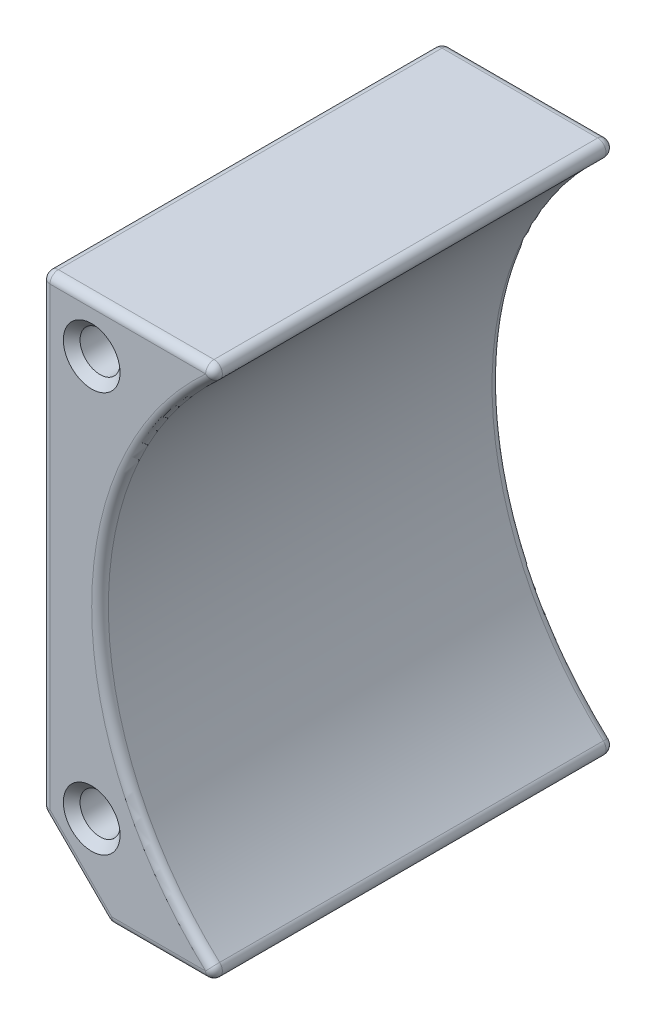
SolidWorks part; units mm, degrees
ref_plane "Front Plane" through (0, 0, 0) normal (0, 0, 1) x (1, 0, 0)
ref_plane "Top Plane" through (0, 0, 0) normal (0, 1, 0) x (1, 0, 0)
ref_plane "Right Plane" through (0, 0, 0) normal (1, 0, 0) x (0, 0, -1)
sketch "Sketch1" plane through (0, 0, 0) normal (0, 0, 1) x (1, 0, 0)
  line L1 (0, 0) -> (17.7546, 0)
  line L2 (0, 0) -> (0, 50.8)
  line L3 (0, 50.8) -> (17.7546, 50.8)
  arc A0 (17.7546, 50.8) -> (17.7546, 0) centre (38.1, 25.4) ccw
  dimension "D4" = 65.0875
  dimension "D1" = 50.8
  dimension "D2" = 25.4
  dimension "D3" = 38.1
extrude "Boss-Extrude1" add sketch "Sketch1" along normal blind 38.1
sketch "Sketch2" plane through (0, 0, 38.1) normal (0, 0, 1) x (1, 0, 0)
  line L0 (17.7546, 50.8) -> (0, 50.8) construction
  line L1 (0, 50.8) -> (0, 0) construction
  line L2 (0, 0) -> (17.7546, 0) construction
  circle A0 centre (4.7625, 46.0375) radius 1.905
  circle A1 centre (4.7625, 7.9375) radius 1.905
  dimension "D4" = 3.81
  dimension "D1" = 4.7625
  dimension "D2" = 4.7625
  dimension "D3" = 7.9375
extrude "Cut-Extrude1" cut sketch "Sketch2" against normal through all
chamfer "Chamfer1" distance 6.35 angle 45 1 edges at (0, 0, 19.05)
fillet "Fillet1" radius 0.7937 15 edges at (3.175, 3.175, 38.1) (0, 6.35, 19.05) (3.175, 3.175, 0) (6.35, 0, 19.05) (17.7546, 0, 19.05) (17.7546, 50.8, 19.05) (0, 50.8, 19.05) (8.8773, 50.8, 38.1) (5.5563, 25.4, 38.1) (12.0523, 0, 38.1) (0, 28.575, 38.1) (8.8773, 50.8, 0) (5.5563, 25.4, 0) (12.0523, 0, 0) (0, 28.575, 0)
chamfer "Chamfer2" distance 0.7937 angle 45 4 edges at (6.6675, 7.9375, 38.1) (6.6675, 7.9375, 0) (6.6675, 46.0375, 38.1) (6.6675, 46.0375, 0)
